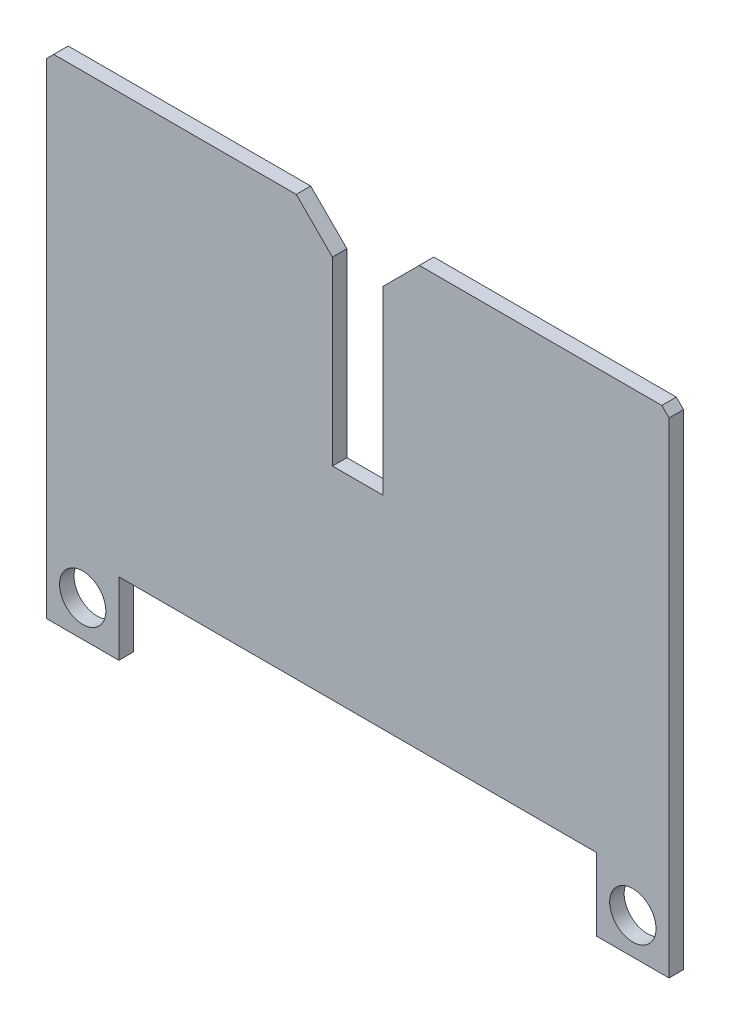
SolidWorks part; units mm, degrees
ref_plane "Front Plane" through (0, 0, 0) normal (0, 0, 1) x (1, 0, 0)
ref_plane "Top Plane" through (0, 0, 0) normal (0, 1, 0) x (1, 0, 0)
ref_plane "Right Plane" through (0, 0, 0) normal (1, 0, 0) x (0, 0, -1)
sketch "Sketch1" plane through (0, 0, 0) normal (0, 0, 1) x (1, 0, 0)
  line L0 (1.75, 5.025) -> (1.75, -7.475)
  line L1 (-21.5, -21.475) -> (21.5, -21.475)
  line L2 (-21.5, -7.475) -> (-21.5, 7.025)
  line L3 (-21, 7.525) -> (-4.25, 7.525)
  line L4 (21.5, -7.475) -> (21.5, 7.025)
  line L5 (0, 0) -> (0, -28.0182) construction
  line L6 (-21.5, -21.475) -> (-21.5, -26.475)
  line L7 (-1.75, 5.025) -> (-1.75, -7.475)
  line L8 (-1.75, -7.475) -> (1.75, -7.475)
  line L9 (-1.75, 7.525) -> (1.75, 7.525) construction
  line L10 (4.25, 7.525) -> (21, 7.525)
  line L11 (-21.5, 7.025) -> (-21, 7.525)
  line L12 (21, 7.525) -> (21.5, 7.025)
  line L13 (-4.25, 7.525) -> (-1.75, 5.025)
  line L14 (1.75, 5.025) -> (4.25, 7.525)
  line L18 (21.5, -21.475) -> (21.5, -7.475)
  line L22 (-21.5, -21.475) -> (-21.5, -7.475)
  line L23 (-21.5, -26.475) -> (-16.5, -26.475)
  line L24 (-16.5, -26.475) -> (-16.5, -21.475)
  line L25 (16.5, -26.475) -> (16.5, -21.475)
  line L26 (21.5, -26.475) -> (16.5, -26.475)
  line L27 (21.5, -21.475) -> (21.5, -26.475)
  circle A0 centre (-19, -23.975) radius 1.6
  circle A1 centre (19, -23.975) radius 1.6
  point P1 (21.5, 7.525)
  point P2 (-21.5, 7.525)
  point P5 (0, -21.475)
  point P15 (0, -7.475)
  point P27 (-16.5, -23.975)
  point P28 (-19, -26.475)
  dimension "D11" = 21.475
  dimension "D12" = 3.2
  dimension "D1" = 29
  dimension "D2" = 43
  dimension "D3" = 3.5
  dimension "D4" = 15
  dimension "D5" = 5
  dimension "D6" = 5
extrude "Boss-Extrude1" add sketch "Sketch1" along normal blind 1 contours L22 L1 L18 L4 L12 L10 L14 L0 L8 L7 L13 L3 L11 L2 | L23 L24 L1 L6 | L27 L1 L25 L26
